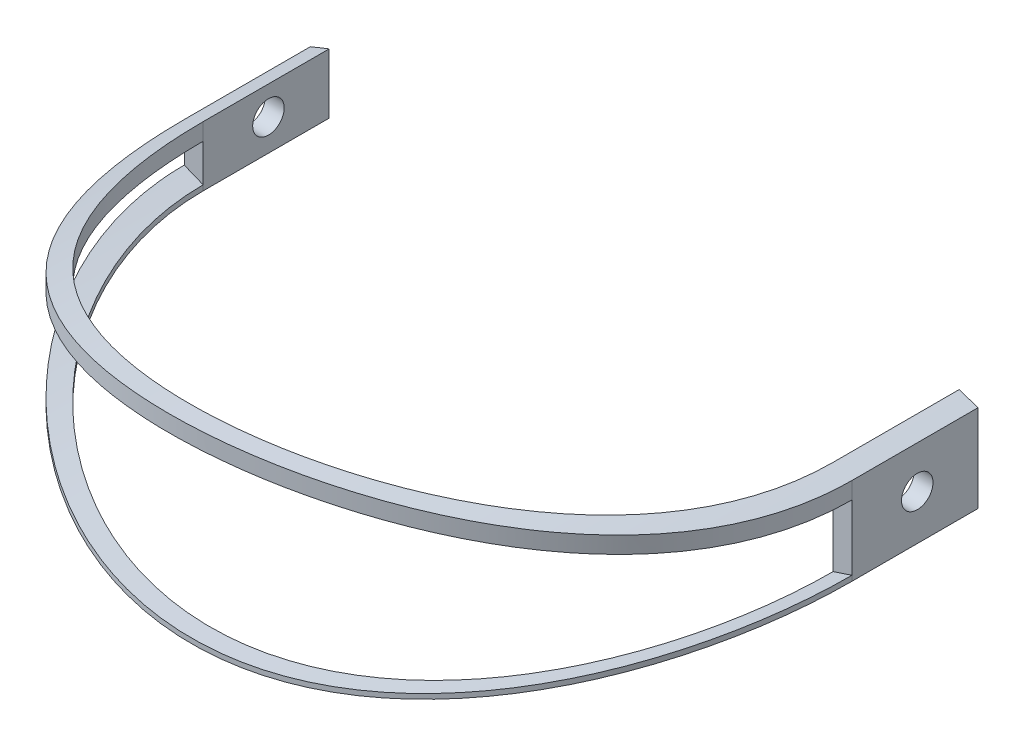
SolidWorks part; units mm, degrees
ref_plane "前视基准面" through (0, 0, 0) normal (0, 0, 1) x (1, 0, 0)
ref_plane "上视基准面" through (0, 0, 0) normal (0, 1, 0) x (1, 0, 0)
ref_plane "右视基准面" through (0, 0, 0) normal (1, 0, 0) x (0, 0, -1)
other "Configuration Table"
sketch "草图1" plane through (0, 0, 0) normal (0, 1, 0) x (1, 0, 0)
  line L0 (-5, 0) -> (-5, 2)
  line L1 (5, 0) -> (5, 2)
  arc A0 (-5, 0) -> (5, 0) centre (0, 0) ccw
  dimension "D1" = 5
  dimension "D2" = 2
extrude "拉伸-薄壁1" add sketch "草图1" along normal mid plane 10 thin thin type one direction reverse wall 0.3
sketch "草图2" plane through (0, 0, 0) normal (0, 0, 1) x (1, 0, 0)
  line L0 (-6.092, 0.2587) -> (6.9847, 0.2587) construction
  arc A0 (-6.092, 0.2587) -> (6.9847, 0.2587) centre (0.4464, 13.7587) ccw
  arc A1 (-6.092, 0.2587) -> (6.9847, 0.2587) centre (0.4464, -13.2413) cw
  dimension "D1" = 15
  dimension "D2" = 3
extrude "切除-拉伸1" cut sketch "草图2" along normal through all both and the other way through all flip side to cut
ref_plane "基准面1" through (0, 0, 0) normal (0, 0, -1) x (-1, 0, 0)
sketch "草图3" plane through (0, 0, 0) normal (0, 0, 1) x (1, 0, 0)
  line L0 (-5.7098, 0.1661) -> (6.6026, 0.1661)
  arc A0 (-5.7098, 0.1661) -> (6.6026, 0.1661) centre (0.4464, 13.7587) ccw
  arc A2 (-5.3, -0.0969) -> (5.3, -0.4343) centre (0.4464, 13.7587) ccw construction
  arc A3 (-5.7098, 0.1661) -> (6.6026, 0.1661) centre (0.4464, -13.4264) cw
  point P0 (6.2217, 0)
extrude "切除-拉伸3" cut sketch "草图3" along normal through all contours A3 L0 | L0 A0
sketch "草图4" plane through (5.3, 0, 0) normal (1, 0, 0) x (0, 0, -1)
  circle A0 centre (1.0359, 0.2816) radius 0.25
  dimension "D1" = 0.5
extrude "切除-拉伸4" cut sketch "草图4" against normal through all
